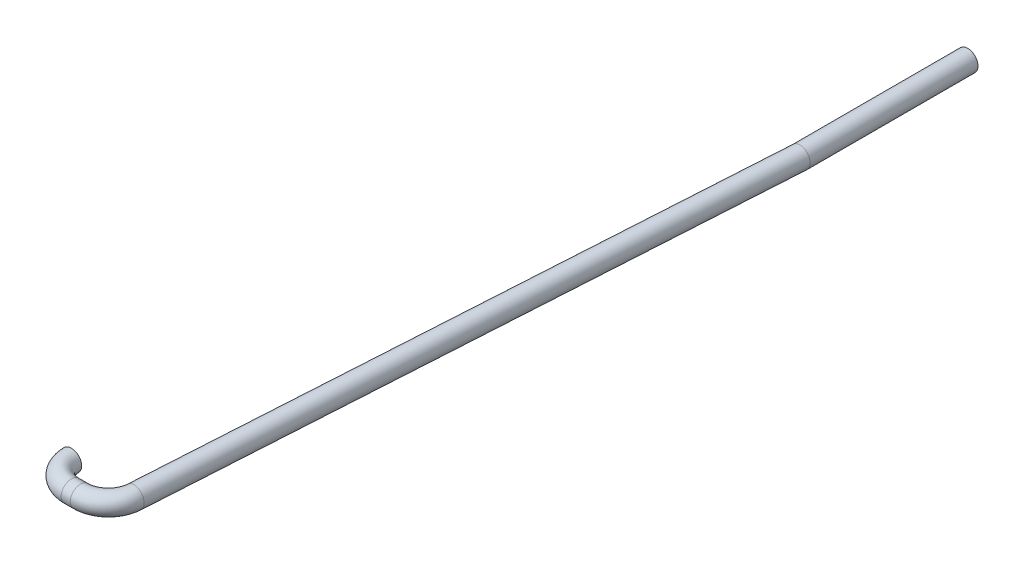
SolidWorks part; units mm, degrees
ref_plane "정면" through (0, 0, 0) normal (0, 0, 1) x (1, 0, 0)
ref_plane "윗면" through (0, 0, 0) normal (0, 1, 0) x (1, 0, 0)
ref_plane "우측면" through (0, 0, 0) normal (1, 0, 0) x (0, 0, -1)
sketch "Sketch1" plane through (0, 0, 0) normal (0, 1, 0) x (1, 0, 0)
  line L0 (-186.1125, -94.4128) -> (-186.1125, 25.5872)
  line L1 (-186.1125, -94.4128) -> (-213.5843, -543.5734)
  line L2 (-233.547, -562.3524) -> (-240.047, -562.3524)
  arc A2 (-213.5843, -543.5734) -> (-233.547, -562.3524) centre (-233.547, -542.3524) cw
  arc A3 (-240.047, -562.3524) -> (-259.047, -543.3524) centre (-240.047, -543.3524) cw
  point P7 (-186.1125, -94.4128)
  point P13 (-214.7329, -562.3524)
  point P23 (-289.407, -562.3524)
  dimension "D2" = 120
  dimension "D3" = 450
  dimension "D8" = 19
  dimension "D4" = 176.5
  dimension "D9" = 6.5
ref_plane "Plane1" through (-259.047, 0, 543.3524) normal (0, 0, -1) x (-1, 0, 0)
sketch "Sketch7" plane through (-259.047, 0, 543.3524) normal (0, 0, -1) x (-1, 0, 0)
  line L0 (0, 0) -> (-19, 0) construction
  circle A0 centre (0, 0) radius 6.34
sweep "Sweep-Thin1" add profiles "Sketch7" path "Sketch1" parameters "D1"=1
